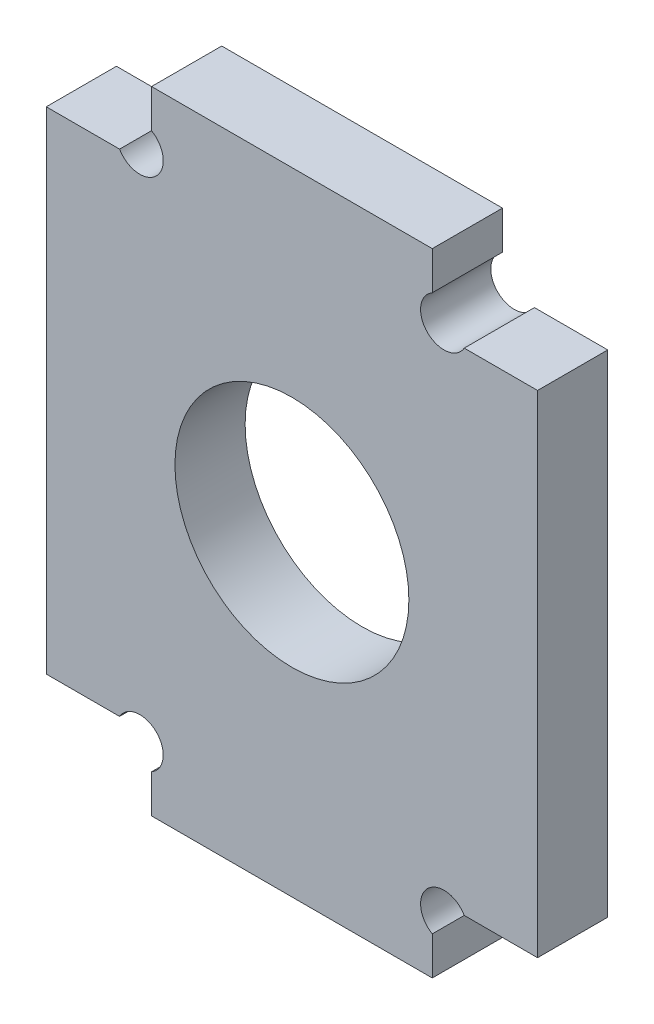
SolidWorks part; units mm, degrees
material "Thornel Mat VMA"
ref_plane "前视基准面" through (0, 0, 0) normal (0, 0, 1) x (1, 0, 0)
ref_plane "上视基准面" through (0, 0, 0) normal (0, 1, 0) x (1, 0, 0)
ref_plane "右视基准面" through (0, 0, 0) normal (1, 0, 0) x (0, 0, -1)
sketch "草图1" plane through (0, 0, 0) normal (0, 0, 1) x (1, 0, 0)
  line L1 (-6, 13.5) -> (6, 13.5)
  line L2 (-6, 13.5) -> (-6, -13.5)
  line L3 (-6, -13.5) -> (6, -13.5)
  line L4 (6, 13.5) -> (6, -13.5)
  line L5 (-6, 13.5) -> (6, -13.5) construction
  line L6 (-6, -13.5) -> (6, 13.5) construction
  line L7 (-10.5, 10.5) -> (10.5, 10.5)
  line L8 (-10.5, 10.5) -> (-10.5, -10.5)
  line L9 (-10.5, -10.5) -> (10.5, -10.5)
  line L10 (10.5, 10.5) -> (10.5, -10.5)
  line L11 (-10.5, 10.5) -> (10.5, -10.5) construction
  line L12 (-10.5, -10.5) -> (10.5, 10.5) construction
  point P0 (0, 0)
  point P5 (0, 0)
  dimension "D1" = 27
  dimension "D2" = 21
  dimension "D3" = 3
  dimension "D4" = 4.5
extrude "凸台-拉伸1" add sketch "草图1" along normal blind 3 contours L2 L7 L4 L1 | L2 L9 L4 L7 | L10 L7 L4 L9 | L9 L2 L3 L4 | L8 L9 L2 L7
sketch "草图2" plane through (0, 0, 3) normal (0, 0, 1) x (1, 0, 0)
  circle A0 centre (0, 0) radius 5
  dimension "D1" = 10
extrude "切除-拉伸1" cut sketch "草图2" against normal through all
sketch "草图3" plane through (0, 0, 3) normal (0, 0, 1) x (1, 0, 0)
  line L0 (0, 13.5) -> (0, -13.5) construction
  line L1 (-6, 13.5) -> (6, 13.5) construction
  line L2 (-6, -13.5) -> (6, -13.5) construction
  line L3 (-10.5, 0) -> (10.5, 0) construction
  line L4 (-10.5, 10.5) -> (-10.5, -10.5) construction
  line L5 (10.5, 10.5) -> (10.5, -10.5) construction
  line L6 (-6, 13.5) -> (-6, 10.5) construction
  line L7 (-10.5, 10.5) -> (-6, 10.5) construction
  circle A0 centre (-6.5, 11) radius 1
  circle A1 centre (6.5, 11) radius 1
  circle A2 centre (6.5, -11) radius 1
  circle A3 centre (-6.5, -11) radius 1
  dimension "D1" = 2
  dimension "D2" = 0.5
  dimension "D3" = 0.5
extrude "切除-拉伸2" cut sketch "草图3" against normal through all
